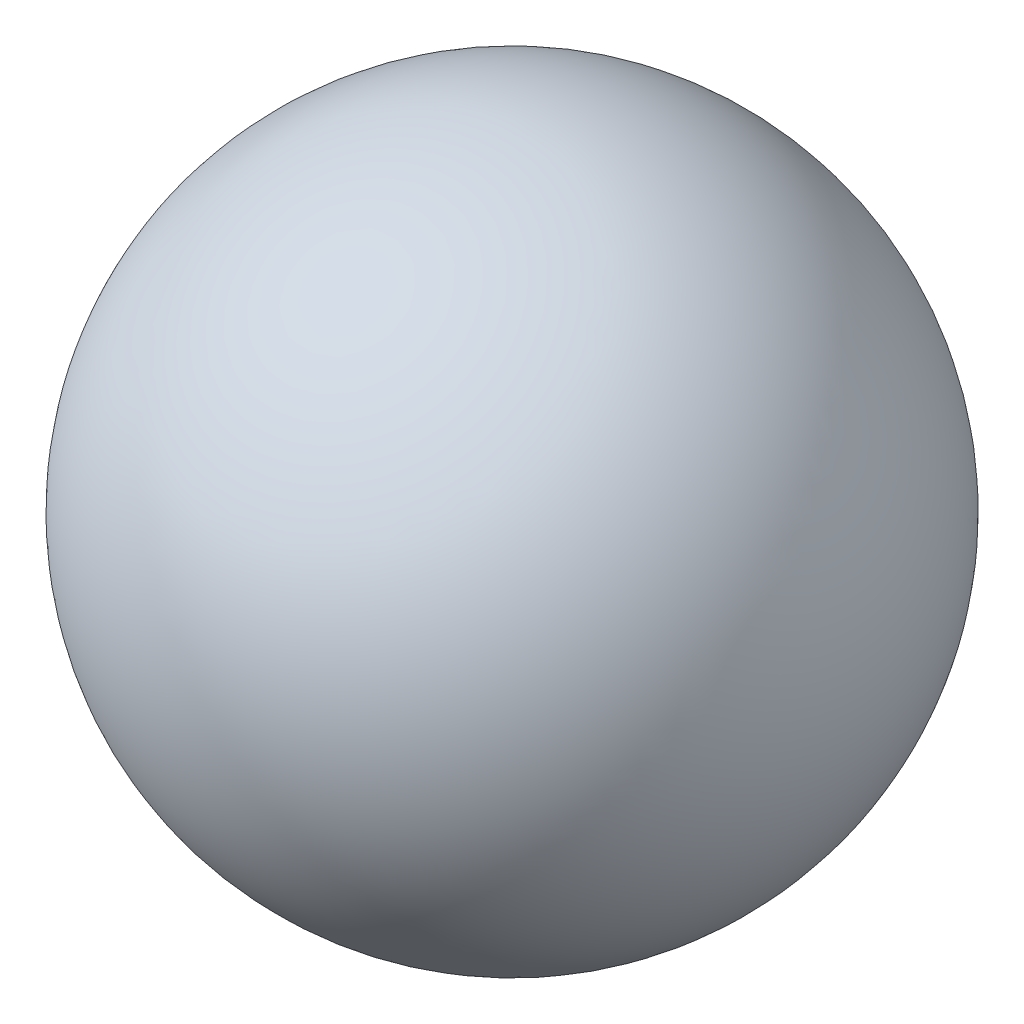
SolidWorks part; units mm, degrees
ref_plane "Front Plane" through (0, 0, 0) normal (0, 0, 1) x (1, 0, 0)
ref_plane "Top Plane" through (0, 0, 0) normal (0, 1, 0) x (1, 0, 0)
ref_plane "Right Plane" through (0, 0, 0) normal (1, 0, 0) x (0, 0, -1)
other "Center of Mass"
sketch "Sketch1" plane through (0, 0, 0) normal (0, 0, 1) x (1, 0, 0)
  line L0 (0, 2250) -> (0, -2250) construction
  line L1 (-710, 0) -> (2575, 0)
  line L2 (2575, 0) -> (2575, 878.5354)
  line L3 (2551.865, 920.705) -> (134.3249, 2460.8479)
  line L4 (-710, -2250) -> (-710, 2250) construction
  line L5 (-710, 0) -> (2575, 0) construction
  line L13 (2575, 0) -> (3997.0823, 0) construction
  arc A0 (2575, 878.5354) -> (2551.865, 920.705) centre (2525, 878.5354) ccw
  arc A1 (134.3249, 2460.8479) -> (-229.9397, 2348.121) centre (0, 2250) ccw
  arc A2 (-229.9397, 2348.121) -> (-710, 0) centre (5272.7174, 0) ccw
  dimension "D3" = 250
  dimension "D5" = 50
  dimension "D7" = 5982.7174
  dimension "D2" = 32.5
  dimension "D6" = 710
  dimension "D1" = 2500
  dimension "D4" = 3285
revolve "Revolve1" add sketch "Sketch1" angle 360 about L13
sketch "Sketch2" plane through (0, 0, 0) normal (0, 0, -1) x (1, 0, 0)
  line L0 (-49379.1983, 0) -> (50620.8017, 0) construction
  arc A0 (11870.8017, 0) -> (-10629.1983, 0) centre (620.8017, 0) ccw
  arc A1 (50620.8017, 0) -> (-49379.1983, 0) centre (620.8017, 0) ccw
  dimension "D1" = 22500
  dimension "D2" = 100000
surface "Surface-Revolve1" sketch "Sketch2" parameters "D1"=360
sketch "Sketch3" plane through (0, 0, 0) normal (0, 0, 1) x (1, 0, 0)
  line L0 (620.8017, 0) -> (-710, 0)
  line L1 (-710, -2250) -> (-710, 2250) construction
  line L2 (-710, -2250) -> (-710, 2250) construction
  dimension "D1" = 1330.8017
equation "\"D\"= 5m"
equation "\"D3@Sketch1\"=0.05 * \"D\""
equation "\"D6@Sketch1\"=0.142*\"D\""
equation "\"D5@Sketch1\"=0.01 * \"D\""
equation "\"D1@Sketch1\"=0.5 * \"D\""
equation "\"D4@Sketch1\"=0.657 * \"D\""
equation "\"D1@Sketch2\"=4.5 * \"D\""
equation "\"D2@Sketch2\"= 20 * \"D\""
